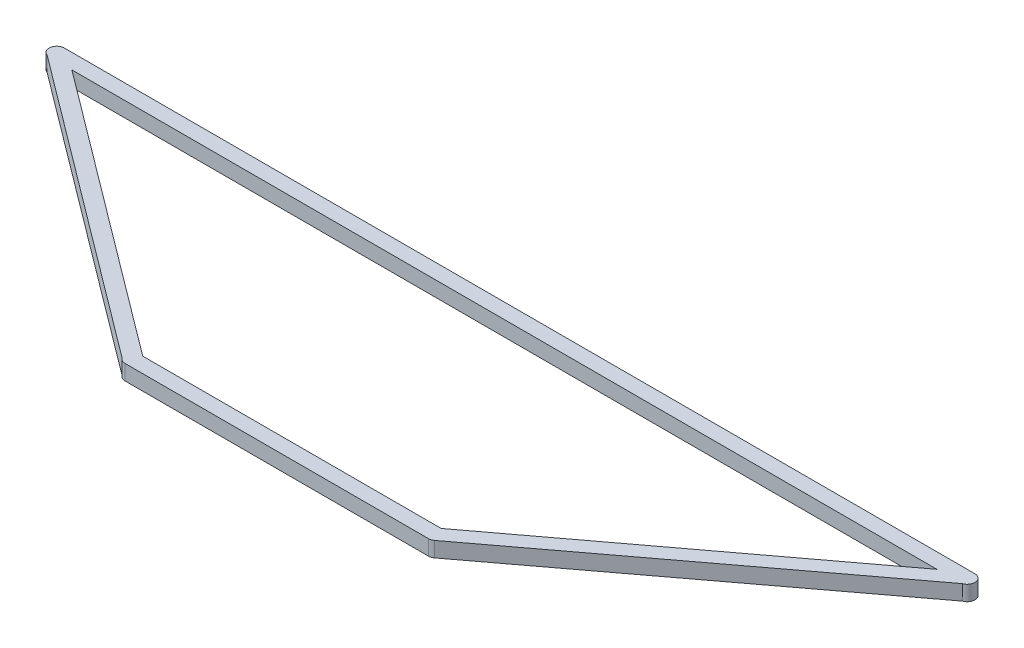
SolidWorks part; units mm, degrees
material "AISI 1020"
ref_plane "Front Plane" through (0, 0, 0) normal (0, 0, 1) x (1, 0, 0)
ref_plane "Top Plane" through (0, 0, 0) normal (0, 1, 0) x (1, 0, 0)
ref_plane "Right Plane" through (0, 0, 0) normal (1, 0, 0) x (0, 0, -1)
sketch "Sketch1" plane through (0, 0, 0) normal (0, 1, 0) x (1, 0, 0)
  line L5 (305.1557, -22.4496) -> (705.1557, -22.4496)
  line L6 (705.1557, -22.4496) -> (705.1557, -42.4496)
  line L7 (705.1557, -42.4496) -> (305.1557, -42.4496)
  line L8 (-94.8443, 277.5504) -> (1105.1557, 277.5504)
  line L9 (1105.1557, 277.5504) -> (1105.1557, 257.5504)
  line L10 (1105.1557, 257.5504) -> (-94.8443, 257.5504)
  line L11 (-94.8443, 257.5504) -> (-94.8443, 277.5504)
  line L12 (-88.8443, 275.5504) -> (311.1557, -24.4496)
  line L13 (311.1557, -24.4496) -> (302.0504, -41.9552)
  line L14 (302.0504, -41.9552) -> (-103.1002, 261.9077)
  line L15 (-103.1002, 261.9077) -> (-88.8443, 275.5504)
  line L17 (1113.4116, 261.9077) -> (711.1642, -40.4432)
  line L18 (711.1642, -40.4432) -> (699.1472, -24.4559)
  line L19 (699.1472, -24.4559) -> (1099.1557, 275.5504)
  line L20 (1099.1557, 275.5504) -> (1113.4116, 261.9077)
  circle A5 centre (-94.8443, 267.5504) radius 10
  circle A6 centre (1105.1557, 267.5504) radius 10
  circle A7 centre (305.1557, -32.4496) radius 10
  circle A8 centre (705.1557, -32.4496) radius 10
  arc A9 (305.1557, -42.4496) -> (305.1557, -22.4496) centre (305.1557, -32.4496) ccw
  dimension "D1" = 20
  dimension "D2" = 20
  dimension "D3" = 20
  dimension "D4" = 20
  dimension "D5" = 300
  dimension "D6" = 300
  dimension "D7" = 400
  dimension "D8" = 1200
  dimension "D9" = 400
  dimension "D10" = 400
extrude "Boss-Extrude2" add sketch "Sketch1" along normal blind 20 contours L15 L12 L13 L14 | L11 L8 L9 L10 | L20 L17 L18 L19 | A9 L5 L6 L7 | A8 | A7 | A5 | A6
